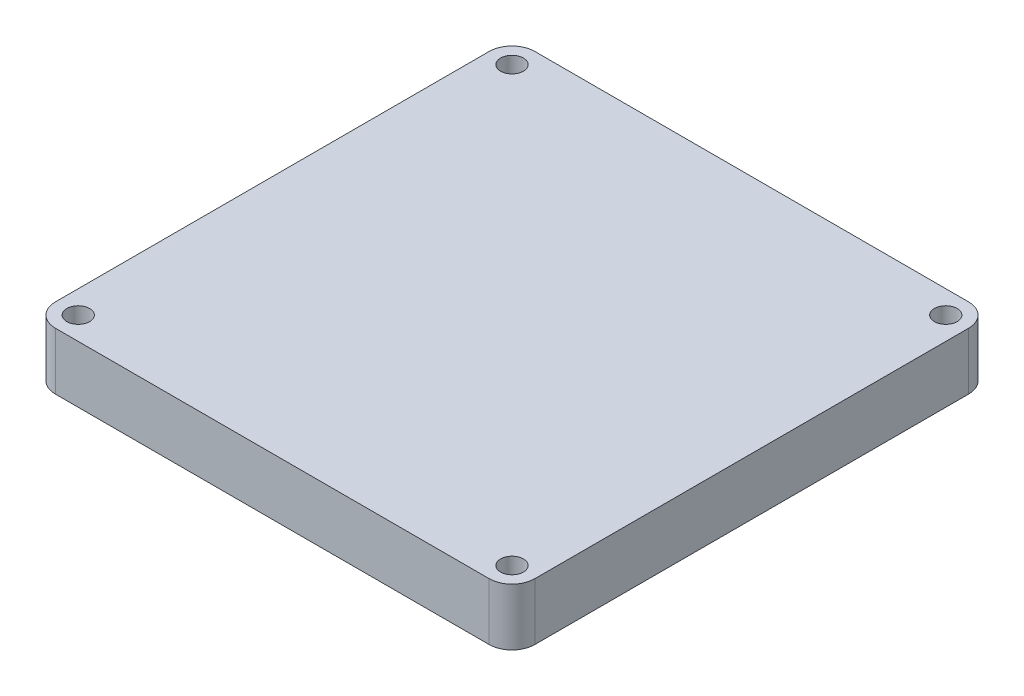
SolidWorks part; units mm, degrees
ref_plane "Front Plane" through (0, 0, 0) normal (0, 0, 1) x (1, 0, 0)
ref_plane "Top Plane" through (0, 0, 0) normal (0, 1, 0) x (1, 0, 0)
ref_plane "Right Plane" through (0, 0, 0) normal (1, 0, 0) x (0, 0, -1)
sketch "Sketch1" plane through (0, 0, 0) normal (0, 1, 0) x (1, 0, 0)
  line L1 (-19, -21) -> (19, -21)
  line L2 (-21, -19) -> (-21, 19)
  line L3 (-19, 21) -> (19, 21)
  line L4 (21, -19) -> (21, 19)
  line L5 (-21, -21) -> (21, 21) construction
  line L6 (-21, 21) -> (21, -21) construction
  arc A0 (19, 21) -> (21, 19) centre (19, 19) cw
  arc A1 (19, -21) -> (21, -19) centre (19, -19) ccw
  arc A2 (-19, -21) -> (-21, -19) centre (-19, -19) cw
  arc A3 (-21, 19) -> (-19, 21) centre (-19, 19) cw
  point P0 (0, 0)
  dimension "D3" = 2
  dimension "D1" = 42
  dimension "D2" = 42
extrude "Boss-Extrude1" add sketch "Sketch1" along normal blind 5
hole_wizard "Ø2.0mm Dowel Hole1" positions "Sketch4" profile "Sketch5" hole size "Ø2.0" standard "ANSI Metric" end condition through all
sketch "Sketch4" plane through (0, 5, 0) normal (0, 1, 0) x (1, 0, 0)
  point P0 (-19, 19)
  dimension "D1" = 19
  dimension "D2" = 19
sketch "Sketch5" plane through (-19, 5, -19) normal (1, 0, 0) x (0, 0, 1)
  line L0 (0, 0) -> (0, 5)
  line L1 (0, 5) -> (1, 5)
  line L2 (1, 5) -> (1, 0)
  line L5 (1, 0) -> (0, 0)
  line L11 (0, -6.35) -> (0, 107.95) construction
  dimension "Thru Hole Dia." = 2
  dimension "Thru Hole Depth" = 5
mirror "Mirror1" about plane through (0, 0, 0) normal (1, 0, 0) of "Ø2.0mm Dowel Hole1"
mirror "Mirror2" about plane through (0, 0, 0) normal (0, 0, 1) of "Mirror1", "Ø2.0mm Dowel Hole1"
